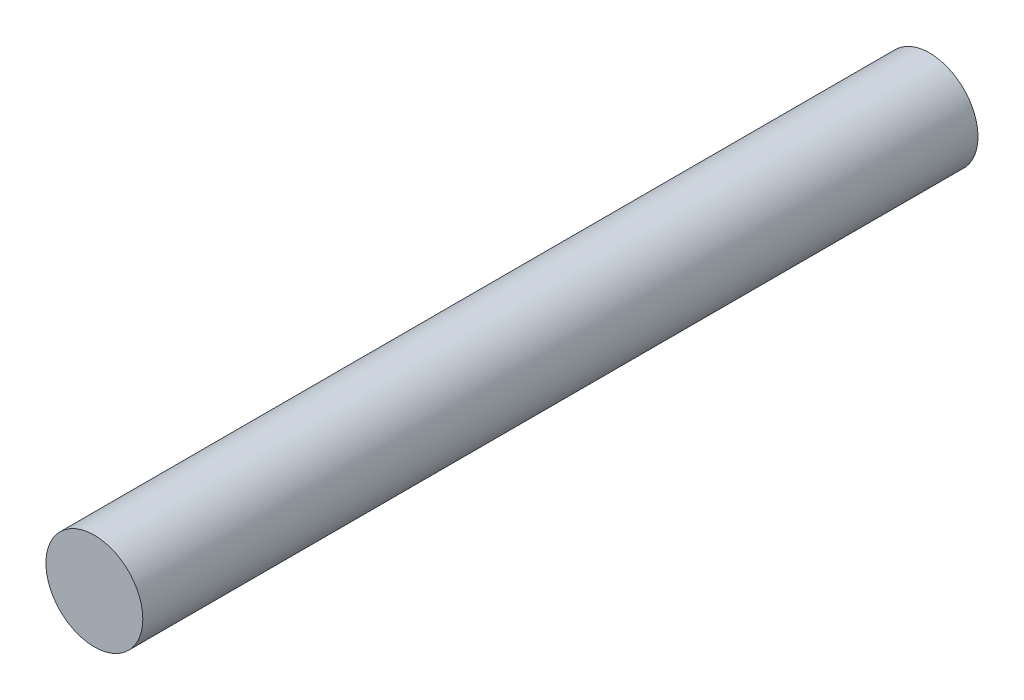
SolidWorks part; units mm, degrees
ref_plane "Front Plane" through (0, 0, 0) normal (0, 0, 1) x (1, 0, 0)
ref_plane "Top Plane" through (0, 0, 0) normal (0, 1, 0) x (1, 0, 0)
ref_plane "Right Plane" through (0, 0, 0) normal (1, 0, 0) x (0, 0, -1)
sketch "Sketch1" plane through (0, 0, 0) normal (0, 0, 1) x (1, 0, 0)
  circle A0 centre (0, 0) radius 4.7879
  dimension "D1" = 9.5758
extrude "Boss-Extrude1" add sketch "Sketch1" along normal blind 82.55
